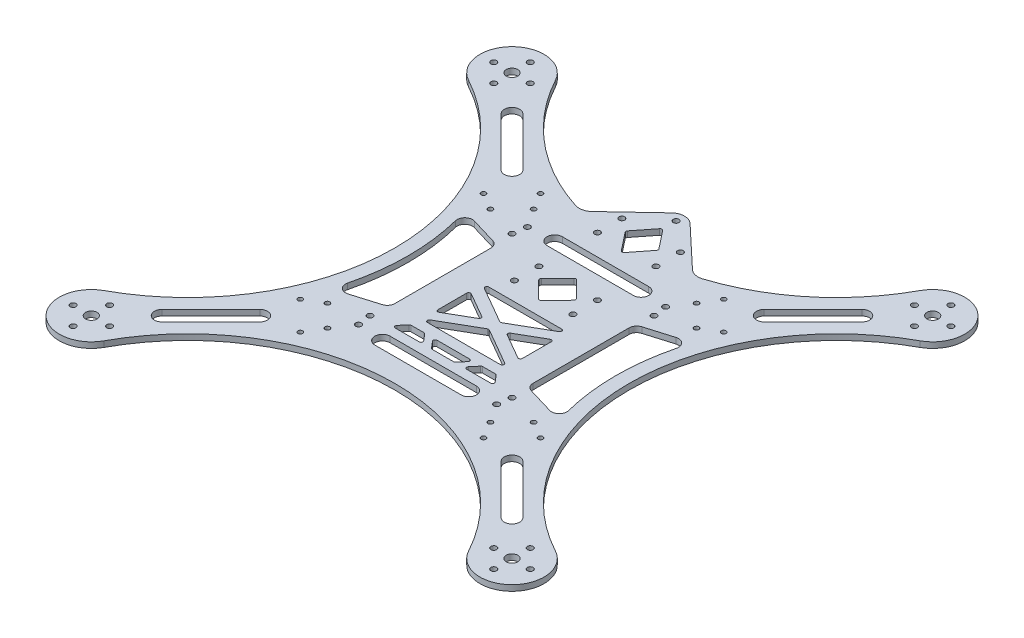
SolidWorks part; units mm, degrees
ref_plane "前视基准面" through (0, 0, 0) normal (0, 0, 1) x (1, 0, 0)
ref_plane "上视基准面" through (0, 0, 0) normal (0, 1, 0) x (1, 0, 0)
ref_plane "右视基准面" through (0, 0, 0) normal (1, 0, 0) x (0, 0, -1)
sketch "草图1" plane through (0, 0, 0) normal (0, 1, 0) x (1, 0, 0)
  line L1 (-109.6016, -109.6016) -> (109.6016, -109.6016) construction
  line L2 (-109.6016, -109.6016) -> (-109.6016, 109.6016) construction
  line L3 (-109.6016, 109.6016) -> (109.6016, 109.6016) construction
  line L4 (109.6016, -109.6016) -> (109.6016, 109.6016) construction
  line L5 (-109.6016, -109.6016) -> (109.6016, 109.6016) construction
  line L6 (-109.6016, 109.6016) -> (109.6016, -109.6016) construction
  line L42 (-4.7985, 87.982) -> (-26.1798, 67.8508)
  line L43 (4.7985, 87.982) -> (26.1798, 67.8508)
  line L52 (-62.579, 47.7297) -> (-47.7297, 62.579) construction
  line L53 (-15.25, 59.75) -> (15.25, 59.75) construction
  line L54 (-15.25, 59.75) -> (-15.25, 29.25) construction
  line L55 (-15.25, 29.25) -> (15.25, 29.25) construction
  line L56 (15.25, 59.75) -> (15.25, 29.25) construction
  line L57 (-15.25, 59.75) -> (15.25, 29.25) construction
  line L58 (-15.25, 29.25) -> (15.25, 59.75) construction
  line L59 (-15.25, 16.5) -> (15.25, 16.5) construction
  line L60 (-15.25, 16.5) -> (-15.25, 72.5) construction
  line L61 (-15.25, 72.5) -> (15.25, 72.5) construction
  line L62 (15.25, 16.5) -> (15.25, 72.5) construction
  line L63 (-15.25, 16.5) -> (15.25, 72.5) construction
  line L64 (-15.25, 72.5) -> (15.25, 16.5) construction
  line L65 (-36, -44) -> (36, -44) construction
  line L66 (-36, -44) -> (-36, 44) construction
  line L67 (-36, 44) -> (36, 44) construction
  line L68 (36, -44) -> (36, 44) construction
  line L69 (-36, -44) -> (36, 44) construction
  line L70 (-36, 44) -> (36, -44) construction
  line L71 (-47.7297, 62.579) -> (-42.4503, 53.7162) construction
  line L72 (-42.4503, 53.7162) -> (-53.7162, 42.4503) construction
  line L73 (-53.7162, 42.4503) -> (-62.579, 47.7297) construction
  line L74 (-62.579, 47.7297) -> (-42.4503, 53.7162) construction
  line L75 (-53.7162, 42.4503) -> (-47.7297, 62.579) construction
  line L76 (0, 0) -> (0, -69.2983) construction
  line L78 (-37, -37) -> (37, -37) construction
  line L79 (-37, -37) -> (-37, 37) construction
  line L80 (-37, 37) -> (37, 37) construction
  line L81 (37, -37) -> (37, 37) construction
  line L82 (-37, -37) -> (37, 37) construction
  line L83 (-37, 37) -> (37, -37) construction
  circle A0 centre (109.6016, 109.6016) radius 89.215 construction
  circle A9 centre (109.6016, -109.6016) radius 89.215 construction
  circle A10 centre (-109.6016, -109.6016) radius 89.215 construction
  circle A11 centre (-109.6016, 109.6016) radius 89.215 construction
  circle A18 centre (0, 85.5) radius 1.5
  circle A19 centre (-15.25, 59.75) radius 1.5
  circle A20 centre (15.25, 59.75) radius 1.5
  circle A21 centre (15.25, 29.25) radius 1.5
  circle A22 centre (-15.25, 29.25) radius 1.5
  circle A23 centre (-15.25, 72.5) radius 1.5
  circle A24 centre (15.25, 72.5) radius 1.5
  circle A25 centre (-15.25, 16.5) radius 1.5
  circle A26 centre (15.25, 16.5) radius 1.5
  circle A28 centre (-109.6016, 109.6016) radius 9.5 construction
  circle A29 centre (-109.6016, 119.1016) radius 1.5
  circle A30 centre (-119.1016, 109.6016) radius 1.5
  circle A31 centre (-109.6016, 100.1016) radius 1.5
  circle A32 centre (-100.1016, 109.6016) radius 1.5
  circle A33 centre (-109.6016, 109.6016) radius 3
  circle A34 centre (109.6016, 119.1016) radius 1.5
  circle A35 centre (109.6016, 109.6016) radius 3
  circle A36 centre (119.1016, 109.6016) radius 1.5
  circle A37 centre (109.6016, 100.1016) radius 1.5
  circle A38 centre (100.1016, 109.6016) radius 1.5
  circle A39 centre (119.1016, -109.6016) radius 1.5
  circle A40 centre (109.6016, -109.6016) radius 3
  circle A41 centre (109.6016, -119.1016) radius 1.5
  circle A42 centre (100.1016, -109.6016) radius 1.5
  circle A43 centre (109.6016, -100.1016) radius 1.5
  circle A44 centre (-109.6016, -119.1016) radius 1.5
  circle A45 centre (-109.6016, -109.6016) radius 3
  circle A46 centre (-119.1016, -109.6016) radius 1.5
  circle A47 centre (-109.6016, -100.1016) radius 1.5
  circle A48 centre (-100.1016, -109.6016) radius 1.5
  circle A49 centre (-36, 44) radius 1.5
  circle A50 centre (36, 44) radius 1.5
  circle A51 centre (-36, -44) radius 1.5
  circle A52 centre (36, -44) radius 1.5
  circle A53 centre (-62.579, 47.7297) radius 1.25
  circle A54 centre (-53.7162, 42.4503) radius 1.25
  circle A55 centre (-42.4503, 53.7162) radius 1.25
  circle A56 centre (-47.7297, 62.579) radius 1.25
  arc A57 (-117.5669, 94.9236) -> (-117.5669, -94.9236) centre (-169.0792, 0) cw
  arc A58 (94.9236, 117.5669) -> (33.1253, 66.2847) centre (0, 169.0792) cw
  arc A59 (117.5669, -94.9236) -> (117.5669, 94.9236) centre (169.0792, 0) cw
  arc A60 (-94.9236, -117.5669) -> (94.9236, -117.5669) centre (0, -169.0792) cw
  arc A61 (-94.9236, 117.5669) -> (-117.5669, 94.9236) centre (-109.6016, 109.6016) ccw
  arc A62 (-117.5669, -94.9236) -> (-94.9236, -117.5669) centre (-109.6016, -109.6016) ccw
  arc A63 (117.5669, 94.9236) -> (94.9236, 117.5669) centre (109.6016, 109.6016) ccw
  arc A64 (94.9236, -117.5669) -> (117.5669, -94.9236) centre (109.6016, -109.6016) ccw
  arc A65 (-33.1253, 66.2847) -> (-94.9236, 117.5669) centre (0, 169.0792) cw
  arc A66 (26.1798, 67.8508) -> (33.1253, 66.2847) centre (30.9783, 72.9473) ccw
  arc A67 (-26.1798, 67.8508) -> (-33.1253, 66.2847) centre (-30.9783, 72.9473) cw
  arc A68 (-4.7985, 87.982) -> (4.7985, 87.982) centre (0, 82.8855) cw
  circle A69 centre (47.7297, 62.579) radius 1.25
  circle A70 centre (62.579, 47.7297) radius 1.25
  circle A71 centre (42.4503, 53.7162) radius 1.25
  circle A72 centre (53.7162, 42.4503) radius 1.25
  circle A73 centre (62.579, -47.7297) radius 1.25
  circle A74 centre (47.7297, -62.579) radius 1.25
  circle A75 centre (53.7162, -42.4503) radius 1.25
  circle A76 centre (42.4503, -53.7162) radius 1.25
  circle A77 centre (-47.7297, -62.579) radius 1.25
  circle A78 centre (-62.579, -47.7297) radius 1.25
  circle A79 centre (-42.4503, -53.7162) radius 1.25
  circle A80 centre (-53.7162, -42.4503) radius 1.25
  circle A82 centre (37, 37) radius 1.5
  circle A83 centre (-37, -37) radius 1.5
  circle A84 centre (37, -37) radius 1.5
  circle A85 centre (-37, 37) radius 1.5
  point P0 (0, 0)
  point P9 (0, 44.5)
  point P11 (0, 0)
  point P19 (0, 0)
  point P26 (0, 0)
  point P27 (-48.0833, 48.0833)
  point P45 (0, 0)
  point P48 (0, 0)
  point P52 (-29.1228, 65.0798)
  point P55 (0, 92.5)
  point P80 (0, 0)
  point P88 (0, 44.5)
  point P144 (0, 0)
  point P145 (0, 0)
  point P154 (0, 0)
  dimension "D2" = 178.43
  dimension "D4" = 85.5
  dimension "D17" = 40
  dimension "D20" = 3
  dimension "D24" = 3
  dimension "D27" = 3
  dimension "D30" = 19
  dimension "D31" = 3
  dimension "D32" = 6
  dimension "D33" = 4
  dimension "D36" = 3
  dimension "D9" = 2.5
  dimension "D10" = 108
  dimension "D13" = 33.4
  dimension "D11" = 4
  dimension "D18" = 7
  dimension "D23" = 3
  dimension "D1" = 310
  dimension "D6" = 10
  dimension "D7" = 21
  dimension "D8" = 21
  dimension "D14" = 68
  dimension "D15" = 44.5
  dimension "D16" = 7
  dimension "D5" = 4
  dimension "D19" = 74
  dimension "D21" = 74
  dimension "D22" = 30.5
  dimension "D25" = 30.5
  dimension "D26" = 56
  dimension "D34" = 88
  dimension "D35" = 72
  dimension "D12" = 4
extrude "凸台-拉伸1" add sketch "草图1" along normal blind 3
sketch "草图2" plane through (0, 3, 0) normal (0, 1, 0) x (1, 0, 0)
  line L0 (-52.5444, 32.9153) -> (-38.8568, 28.8332)
  line L1 (-36, 25) -> (-36, -25)
  line L2 (-38.8568, -28.8332) -> (-52.5444, -32.9153)
  line L3 (0, 0) -> (0, 37.9223) construction
  line L4 (36, 25) -> (36, -25)
  line L5 (52.5444, 32.9153) -> (38.8568, 28.8332)
  line L6 (38.8568, -28.8332) -> (52.5444, -32.9153)
  line L7 (-22.5, 44.75) -> (22.5, 44.75) construction
  line L8 (-22.5, 48.75) -> (22.5, 48.75)
  line L9 (-22.5, 40.75) -> (22.5, 40.75)
  line L10 (-22.5, -45) -> (22.5, -45) construction
  line L11 (-22.5, -41) -> (22.5, -41)
  line L12 (-22.5, -49) -> (22.5, -49)
  line L25 (-61.4634, -9.1014) -> (61.4634, -9.1014) construction
  line L26 (-19, 6.8986) -> (19, 6.8986)
  line L27 (-0.4995, -5.8663) -> (-19.4863, 5.0817)
  line L28 (19.4863, 5.0817) -> (0.4995, -5.8663)
  line L29 (-0.4995, -12.3365) -> (-19.4863, -23.2845)
  line L30 (19.4863, -23.2845) -> (0.4995, -12.3365)
  line L31 (-19, -25.1014) -> (19, -25.1014)
  line L32 (-7.4934, -8.2351) -> (-20.5005, -0.7351)
  line L33 (-22, -1.6014) -> (-22, -16.6014)
  line L34 (-20.5005, -17.4677) -> (-7.4934, -9.9677)
  line L35 (22, -1.6014) -> (22, -16.6014)
  line L36 (7.4934, -8.2351) -> (20.5005, -0.7351)
  line L37 (20.5005, -17.4677) -> (7.4934, -9.9677)
  line L38 (-109.6016, -109.6016) -> (109.6016, 109.6016) construction
  line L40 (109.6016, -109.6016) -> (-109.6016, 109.6016) construction
  line L42 (-91.1653, -91.1653) -> (-65.7095, -65.7095) construction
  line L43 (-93.9938, -88.3369) -> (-68.5379, -62.8811)
  line L44 (-88.3369, -93.9938) -> (-62.8811, -68.5379)
  line L49 (-91.1653, 91.1653) -> (-65.7095, 65.7095) construction
  line L50 (-88.3369, 93.9938) -> (-62.8811, 68.5379)
  line L51 (-93.9938, 88.3369) -> (-68.5379, 62.8811)
  line L52 (91.1653, 91.1653) -> (65.7095, 65.7095) construction
  line L53 (93.9938, 88.3369) -> (68.5379, 62.8811)
  line L54 (88.3369, 93.9938) -> (62.8811, 68.5379)
  line L55 (91.1653, -91.1653) -> (65.7095, -65.7095) construction
  line L56 (88.3369, -93.9938) -> (62.8811, -68.5379)
  line L57 (93.9938, -88.3369) -> (68.5379, -62.8811)
  line L62 (-0.7857, 77.752) -> (-8.1732, 68.3686)
  line L63 (-8.1732, 67.1314) -> (-0.7857, 57.748)
  line L64 (0.7857, 77.752) -> (8.1732, 68.3686)
  line L65 (8.1732, 67.1314) -> (0.7857, 57.748)
  line L66 (-24.8315, -36) -> (-12.4175, -36)
  line L67 (0.7143, 14.479) -> (9.1122, 23.0501)
  line L68 (-0.7143, 14.479) -> (-9.1122, 23.0501)
  line L69 (-9.1122, 24.4499) -> (-0.7143, 33.021)
  line L70 (9.1122, 24.4499) -> (0.7143, 33.021)
  line L71 (-25.5921, -34.3507) -> (-22.6909, -30.9521)
  line L72 (-21.9303, -30.6014) -> (-15.3188, -30.6014)
  line L73 (22.6909, -30.9521) -> (25.5921, -34.3507)
  line L74 (-14.5582, -30.9521) -> (-11.657, -34.3507)
  line L75 (-9.1917, -32.2507) -> (-6.2904, -35.6493)
  line L76 (-8.4311, -30.6014) -> (8.4491, -30.6014)
  line L77 (-5.5299, -36) -> (5.5478, -36)
  line L78 (9.2096, -32.2507) -> (6.3084, -35.6493)
  line L79 (11.6769, -34.3507) -> (14.5781, -30.9521)
  line L80 (15.3387, -30.6014) -> (21.9303, -30.6014)
  line L81 (12.4374, -36) -> (24.8315, -36)
  arc A0 (-57.5663, 28.1045) -> (-57.5663, -28.1045) centre (-169.0792, 0) cw
  arc A1 (-117.5669, -94.9236) -> (-117.5669, 94.9236) centre (-169.0792, 0) ccw construction
  arc A2 (-57.5663, -28.1045) -> (-52.5444, -32.9153) centre (-53.6875, -29.0821) ccw
  arc A3 (-36, -25) -> (-38.8568, -28.8332) centre (-40, -25) cw
  arc A4 (-38.8568, 28.8332) -> (-36, 25) centre (-40, 25) cw
  arc A5 (-57.5663, 28.1045) -> (-52.5444, 32.9153) centre (-53.6875, 29.0821) cw
  arc A6 (38.8568, 28.8332) -> (36, 25) centre (40, 25) ccw
  arc A7 (57.5663, 28.1045) -> (52.5444, 32.9153) centre (53.6875, 29.0821) ccw
  arc A8 (57.5663, 28.1045) -> (57.5663, -28.1045) centre (169.0792, 0) ccw
  arc A9 (57.5663, -28.1045) -> (52.5444, -32.9153) centre (53.6875, -29.0821) cw
  arc A10 (36, -25) -> (38.8568, -28.8332) centre (40, -25) ccw
  arc A11 (-22.5, 48.75) -> (-22.5, 40.75) centre (-22.5, 44.75) ccw
  arc A12 (22.5, 40.75) -> (22.5, 48.75) centre (22.5, 44.75) ccw
  circle A13 centre (-15.25, 59.75) radius 1.5 construction
  arc A14 (-22.5, -41) -> (-22.5, -49) centre (-22.5, -45) ccw
  arc A15 (22.5, -49) -> (22.5, -41) centre (22.5, -45) ccw
  circle A16 centre (-37, -37) radius 1.5 construction
  arc A26 (19, 6.8986) -> (19.4863, 5.0817) centre (19, 5.9251) cw
  arc A27 (-19, 6.8986) -> (-19.4863, 5.0817) centre (-19, 5.9251) ccw
  arc A28 (-0.4995, -5.8663) -> (0.4995, -5.8663) centre (0, -5) ccw
  arc A29 (117.5669, 94.9236) -> (117.5669, -94.9236) centre (169.0792, 0) ccw construction
  arc A30 (-0.4995, -12.3365) -> (0.4995, -12.3365) centre (0, -13.2028) cw
  arc A31 (19, -25.1014) -> (19.4863, -23.2845) centre (19, -24.1278) ccw
  arc A32 (-19, -25.1014) -> (-19.4863, -23.2845) centre (-19, -24.1278) cw
  arc A33 (-22, -16.6014) -> (-20.5005, -17.4677) centre (-21, -16.6014) ccw
  arc A34 (-7.4934, -8.2351) -> (-7.4934, -9.9677) centre (-7.9929, -9.1014) cw
  arc A35 (-20.5005, -0.7351) -> (-22, -1.6014) centre (-21, -1.6014) ccw
  arc A36 (20.5005, -0.7351) -> (22, -1.6014) centre (21, -1.6014) cw
  arc A37 (22, -16.6014) -> (20.5005, -17.4677) centre (21, -16.6014) cw
  arc A38 (7.4934, -8.2351) -> (7.4934, -9.9677) centre (7.9929, -9.1014) ccw
  arc A39 (-93.9938, -88.3369) -> (-88.3369, -93.9938) centre (-91.1653, -91.1653) ccw
  arc A40 (-62.8811, -68.5379) -> (-68.5379, -62.8811) centre (-65.7095, -65.7095) ccw
  arc A43 (-88.3369, 93.9938) -> (-93.9938, 88.3369) centre (-91.1653, 91.1653) ccw
  arc A44 (-68.5379, 62.8811) -> (-62.8811, 68.5379) centre (-65.7095, 65.7095) ccw
  arc A45 (93.9938, 88.3369) -> (88.3369, 93.9938) centre (91.1653, 91.1653) ccw
  arc A46 (62.8811, 68.5379) -> (68.5379, 62.8811) centre (65.7095, 65.7095) ccw
  arc A47 (88.3369, -93.9938) -> (93.9938, -88.3369) centre (91.1653, -91.1653) ccw
  arc A48 (68.5379, -62.8811) -> (62.8811, -68.5379) centre (65.7095, -65.7095) ccw
  arc A49 (-0.7857, 57.748) -> (0.7857, 57.748) centre (0, 58.3666) ccw
  arc A50 (8.1732, 68.3686) -> (8.1732, 67.1314) centre (7.3875, 67.75) cw
  arc A51 (-8.1732, 68.3686) -> (-8.1732, 67.1314) centre (-7.3875, 67.75) ccw
  arc A52 (-0.7857, 77.752) -> (0.7857, 77.752) centre (0, 77.1334) cw
  arc A53 (0.7143, 14.479) -> (-0.7143, 14.479) centre (0, 15.1789) cw
  arc A54 (9.1122, 23.0501) -> (9.1122, 24.4499) centre (8.398, 23.75) ccw
  arc A55 (-9.1122, 23.0501) -> (-9.1122, 24.4499) centre (-8.398, 23.75) cw
  arc A56 (-0.7143, 33.021) -> (0.7143, 33.021) centre (0, 32.3211) cw
  circle A57 centre (37, -37) radius 1.5 construction
  arc A58 (-14.5582, -30.9521) -> (-15.3188, -30.6014) centre (-15.3188, -31.6014) ccw
  arc A59 (-22.6909, -30.9521) -> (-21.9303, -30.6014) centre (-21.9303, -31.6014) cw
  arc A60 (6.3084, -35.6493) -> (5.5478, -36) centre (5.5478, -35) cw
  arc A61 (-6.2904, -35.6493) -> (-5.5299, -36) centre (-5.5299, -35) ccw
  arc A62 (-9.1917, -32.2507) -> (-8.4311, -30.6014) centre (-8.4311, -31.6014) cw
  arc A63 (9.2096, -32.2507) -> (8.4491, -30.6014) centre (8.4491, -31.6014) ccw
  arc A64 (14.5781, -30.9521) -> (15.3387, -30.6014) centre (15.3387, -31.6014) cw
  arc A65 (21.9303, -30.6014) -> (22.6909, -30.9521) centre (21.9303, -31.6014) cw
  arc A66 (24.8315, -36) -> (25.5921, -34.3507) centre (24.8315, -35) ccw
  arc A67 (11.6769, -34.3507) -> (12.4374, -36) centre (12.4374, -35) ccw
  arc A68 (-11.657, -34.3507) -> (-12.4175, -36) centre (-12.4175, -35) cw
  arc A69 (-24.8315, -36) -> (-25.5921, -34.3507) centre (-24.8315, -35) cw
  point P13 (-59.5347, -35)
  point P20 (-59.5347, 35)
  point P36 (-36, 0)
  point P37 (0, 44.75)
  point P42 (0, -45)
  point P73 (-5.991, -9.1014)
  point P88 (0, 0)
  point P102 (0, -9.1014)
  point P103 (0, 0)
  point P105 (-78.4374, -78.4374)
  point P116 (-78.4374, 78.4374)
  point P123 (78.4374, 78.4374)
  point P127 (0, 0)
  point P131 (78.4374, -78.4374)
  point P136 (0, 0)
  point P140 (0, 44.75)
  point P144 (0, -36)
  point P148 (0, 56.75)
  point P151 (8.6603, 67.75)
  point P156 (0, 78.75)
  point P166 (0, 13.75)
  point P171 (-9.798, 23.75)
  point P174 (0, 33.75)
  point P184 (-14.8576, -30.6014)
  point P187 (-22.3915, -30.6014)
  point P190 (6.009, -36)
  point P193 (-5.991, -36)
  point P196 (-10.5996, -30.6014)
  point P201 (14.8775, -30.6014)
  point P206 (27, -36)
  point P209 (10.269, -36)
  point P214 (-27, -36)
  dimension "D1" = 115
  dimension "D4" = 4
  dimension "D7" = 4
  dimension "D10" = 4
  dimension "D12" = 16
  dimension "D17" = 1
  dimension "D13" = 1
  dimension "D22" = 4
  dimension "D28" = 1
  dimension "D32" = 1
  dimension "D42" = 1
  dimension "D2" = 70
  dimension "D3" = 36
  dimension "D5" = 50
  dimension "D6" = 45
  dimension "D8" = 15
  dimension "D9" = 45
  dimension "D11" = 8
  dimension "D14" = 38
  dimension "D15" = 15
  dimension "D16" = 14
  dimension "D18" = 9.1014
  dimension "D19" = 5.5457
  dimension "D20" = 5
  dimension "D21" = 36
  dimension "D23" = 78.4374
  dimension "D24" = 4
  dimension "D25" = 14
  dimension "D26" = 12
  dimension "D27" = 34
  dimension "D29" = 31
  dimension "D30" = 14
  dimension "D31" = 11
  dimension "D33" = 9
  dimension "D34" = 5.5
  dimension "D35" = 3.24
  dimension "D36" = 7.0981
  dimension "D37" = 3.2385
  dimension "D38" = 12
  dimension "D39" = 10
  dimension "D40" = 10
  dimension "D41" = 7.5339
extrude "切除-拉伸1" cut sketch "草图2" against normal through all
